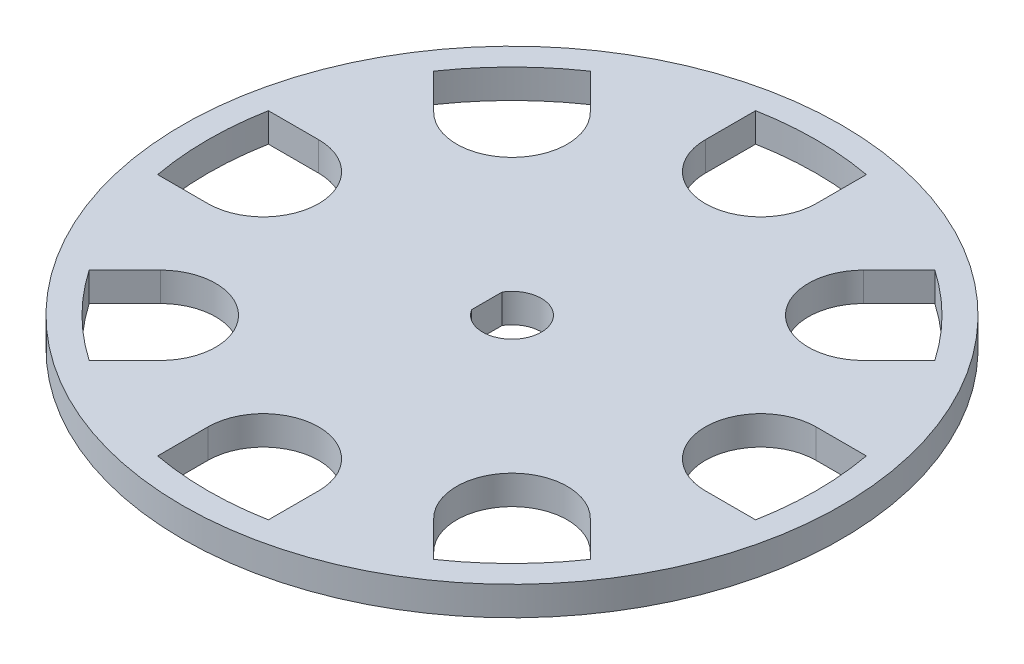
SolidWorks part; units mm, degrees
ref_plane "Front Plane" through (0, 0, 0) normal (0, 0, 1) x (1, 0, 0)
ref_plane "Top Plane" through (0, 0, 0) normal (0, 1, 0) x (1, 0, 0)
ref_plane "Right Plane" through (0, 0, 0) normal (1, 0, 0) x (0, 0, -1)
sketch "Sketch2" plane through (0, 0, 0) normal (0, 1, 0) x (1, 0, 0)
  line L0 (-20.7141, 20.7141) -> (-27.0642, 11.2104) construction
  line L1 (29.2941, 0) -> (27.0642, 11.2104) construction
  line L2 (27.0642, 11.2104) -> (20.7141, 20.7141) construction
  line L3 (20.7141, 20.7141) -> (11.2104, 27.0642) construction
  line L4 (11.2104, 27.0642) -> (0, 29.2941) construction
  line L5 (0, 29.2941) -> (-11.2104, 27.0642) construction
  line L6 (-11.2104, 27.0642) -> (-20.7141, 20.7141) construction
  line L7 (-27.0642, 11.2104) -> (-29.2941, 0) construction
  line L8 (-29.2941, 0) -> (-27.0642, -11.2104) construction
  line L9 (-27.0642, -11.2104) -> (-20.7141, -20.7141) construction
  line L10 (-20.7141, -20.7141) -> (-11.2104, -27.0642) construction
  line L11 (-11.2104, -27.0642) -> (0, -29.2941) construction
  line L12 (0, -29.2941) -> (11.2104, -27.0642) construction
  line L13 (11.2104, -27.0642) -> (20.7141, -20.7141) construction
  line L14 (20.7141, -20.7141) -> (27.0642, -11.2104) construction
  line L15 (27.0642, -11.2104) -> (29.2941, 0) construction
  circle A0 centre (0, 0) radius 28.7312 construction
  circle A1 centre (0, 0) radius 29.2941
  circle A2 centre (0, 0) radius 31.75
  dimension "D1" = 63.5
extrude "Boss-Extrude1" add sketch "Sketch2" along normal blind 2.794 contours A2 A1 | A1
sketch "Sketch3" plane through (0, 3.175, 0) normal (0, 1, 0) x (1, 0, 0)
  line L0 (0, 0) -> (0, -29.2941) construction
  line L1 (5.334, -23.9601) -> (5.334, -28.8044)
  line L2 (-5.334, -23.9601) -> (-5.334, -28.8044)
  line L3 (-20.7141, -13.1707) -> (-24.1395, -16.5961)
  line L4 (-13.1707, -20.7141) -> (-16.5961, -24.1395)
  line L5 (-23.9601, 5.334) -> (-28.8044, 5.334)
  line L6 (-23.9601, -5.334) -> (-28.8044, -5.334)
  line L7 (-13.1707, 20.7141) -> (-16.5961, 24.1395)
  line L8 (-20.7141, 13.1707) -> (-24.1395, 16.5961)
  line L9 (5.334, 23.9601) -> (5.334, 28.8044)
  line L10 (-5.334, 23.9601) -> (-5.334, 28.8044)
  line L11 (20.7141, 13.1707) -> (24.1395, 16.5961)
  line L12 (13.1707, 20.7141) -> (16.5961, 24.1395)
  line L13 (23.9601, -5.334) -> (28.8044, -5.334)
  line L14 (23.9601, 5.334) -> (28.8044, 5.334)
  line L15 (13.1707, -20.7141) -> (16.5961, -24.1395)
  line L16 (20.7141, -13.1707) -> (24.1395, -16.5961)
  circle A0 centre (0, 0) radius 29.2941 construction
  circle A1 centre (0, -23.9601) radius 5.334 construction
  arc A2 (-5.334, -23.9601) -> (5.334, -23.9601) centre (0, -23.9601) cw
  arc A3 (5.334, -28.8044) -> (-5.334, -28.8044) centre (0, 0) cw
  arc A4 (-16.5961, -24.1395) -> (-24.1395, -16.5961) centre (0, 0) cw
  arc A5 (-20.7141, -13.1707) -> (-13.1707, -20.7141) centre (-16.9424, -16.9424) cw
  arc A6 (-28.8044, -5.334) -> (-28.8044, 5.334) centre (0, 0) cw
  arc A7 (-23.9601, 5.334) -> (-23.9601, -5.334) centre (-23.9601, 0) cw
  arc A8 (-24.1395, 16.5961) -> (-16.5961, 24.1395) centre (0, 0) cw
  arc A9 (-13.1707, 20.7141) -> (-20.7141, 13.1707) centre (-16.9424, 16.9424) cw
  arc A10 (-5.334, 28.8044) -> (5.334, 28.8044) centre (0, 0) cw
  arc A11 (5.334, 23.9601) -> (-5.334, 23.9601) centre (0, 23.9601) cw
  arc A12 (16.5961, 24.1395) -> (24.1395, 16.5961) centre (0, 0) cw
  arc A13 (20.7141, 13.1707) -> (13.1707, 20.7141) centre (16.9424, 16.9424) cw
  arc A14 (28.8044, 5.334) -> (28.8044, -5.334) centre (0, 0) cw
  arc A15 (23.9601, -5.334) -> (23.9601, 5.334) centre (23.9601, 0) cw
  arc A16 (24.1395, -16.5961) -> (16.5961, -24.1395) centre (0, 0) cw
  arc A17 (13.1707, -20.7141) -> (20.7141, -13.1707) centre (16.9424, -16.9424) cw
  point P64 (0, 0)
  dimension "D1" = 8
  dimension "D2" = 58.5882
  dimension "D3" = 10.668
extrude "Cut-Extrude1" cut sketch "Sketch3" against normal through all
sketch "Sketch4" plane through (0, 3.175, 0) normal (0, 1, 0) x (1, 0, 0)
  line L0 (0, 0) -> (2.8257, 0) construction
  line L1 (0, 0) -> (-2.413, 0) construction
  line L2 (-2.413, -1.4705) -> (-2.413, 1.4705)
  circle A0 centre (0, 0) radius 2.8257 construction
  arc A1 (-2.413, -1.4705) -> (-2.413, 1.4705) centre (0, 0) ccw
  point P8 (-2.413, 0)
  dimension "D1" = 2.413
  dimension "D2" = 2.8257
extrude "Cut-Extrude2" cut sketch "Sketch4" against normal through all contours L2 A1
